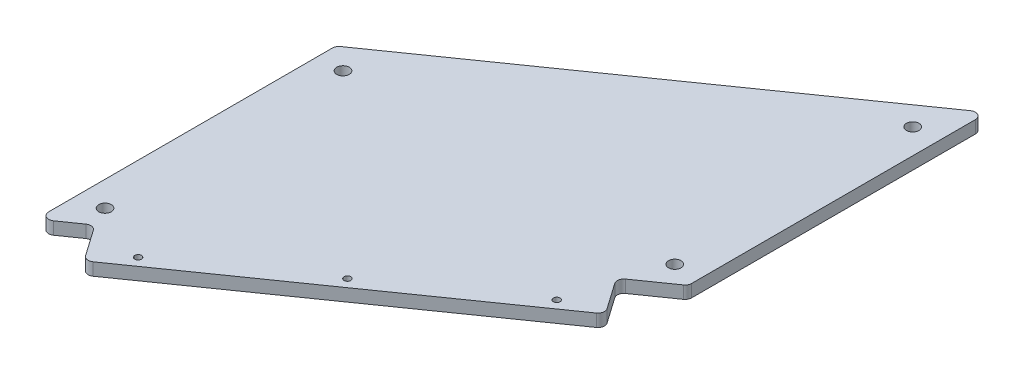
SolidWorks part; units mm, degrees
material "ABS PC"
ref_plane "Front" through (0, 0, 0) normal (0, 0, 1) x (1, 0, 0)
ref_plane "Top" through (0, 0, 0) normal (0, 1, 0) x (1, 0, 0)
ref_plane "Right" through (0, 0, 0) normal (1, 0, 0) x (0, 0, -1)
sketch "Sketch1" plane through (0, 0, 0) normal (0, 1, 0) x (1, 0, 0)
  line L0 (0, 0) -> (0, 359.0634)
  line L1 (0, 0) -> (388.9375, 272.337)
  line L2 (388.9375, 272.337) -> (388.9375, 631.4004)
  line L3 (0, 38.7596) -> (388.9375, 311.0966) construction
  line L4 (0, 54.2634) -> (388.9375, 326.6004) construction
  line L5 (0, 0) -> (-115.0997, 0) construction
  line L6 (0, 359.0634) -> (388.9375, 631.4004)
  dimension "D1" = 388.9375
  dimension "D2" = 145
  dimension "D3" = 31.75
  dimension "D4" = 12.7
  dimension "D5" = 304.8
extrude "Boss-Extrude1" add sketch "Sketch1" along normal blind 12.7
sketch "Sketch2" plane through (0, 12.7, 0) normal (0, 1, 0) x (1, 0, 0)
  line L0 (0, 38.7596) -> (388.9375, 311.0966) construction
  line L1 (0, 359.0634) -> (0, 0) construction
  line L2 (388.9375, 272.337) -> (388.9375, 631.4004) construction
  line L3 (0, 55.1937) -> (388.9375, 327.5306) construction
  line L4 (0, 0) -> (388.9375, 272.337) construction
  line L5 (35.0561, 79.7402) -> (60.9887, 42.7047)
  line L6 (0, 55.1937) -> (35.0561, 79.7402)
  line L7 (0, 55.1937) -> (0, 0)
  line L8 (0, 0) -> (60.9887, 42.7047)
  line L9 (388.9375, 327.5306) -> (346.0997, 297.5353)
  line L10 (346.0997, 297.5353) -> (372.0322, 260.4998)
  line L11 (372.0322, 260.4998) -> (388.9375, 272.337)
  line L12 (388.9375, 272.337) -> (388.9375, 327.5306)
  dimension "D1" = 31.75
  dimension "D2" = 13.462
  dimension "D3" = 74.4534
  dimension "D4" = 20.6375
extrude "Cut-Extrude1" cut sketch "Sketch2" against normal through all
sketch "Sketch3" plane through (0, 12.7, 0) normal (0, 1, 0) x (1, 0, 0)
  line L0 (54.6148, 51.8076) -> (365.6584, 269.6026) construction
  line L1 (60.9887, 42.7047) -> (35.0561, 79.7402) construction
  line L2 (346.0997, 297.5353) -> (372.0322, 260.4998) construction
  line L3 (60.9887, 42.7047) -> (372.0322, 260.4998) construction
  line L4 (25.4, 340.9437) -> (25.4, 99.6437) construction
  line L5 (0, 359.0634) -> (0, 55.1937) construction
  line L6 (363.5375, 580.6004) -> (363.5375, 339.3004) construction
  line L7 (388.9375, 327.5306) -> (388.9375, 631.4004) construction
  circle A0 centre (210.1366, 160.7051) radius 3.3782
  circle A1 centre (334.9754, 248.1181) radius 3.3782
  circle A2 centre (85.2978, 73.292) radius 3.3782
  circle A3 centre (25.4, 99.6437) radius 6.35
  circle A4 centre (25.4, 340.9437) radius 6.35
  circle A5 centre (363.5375, 339.3004) radius 6.35
  circle A6 centre (363.5375, 580.6004) radius 6.35
  dimension "D2" = 6.7564
  dimension "D5" = 12.7
  dimension "D1" = 11.1125
  dimension "D3" = 152.4
  dimension "D4" = 152.4
  dimension "D6" = 25.4
  dimension "D7" = 44.45
  dimension "D8" = 241.3
  dimension "D9" = 25.4
  dimension "D10" = 50.8
extrude "Cut-Extrude2" cut sketch "Sketch3" against normal through all
fillet "Fillet1" radius 6.604 8 edges at (60.9887, 6.35, -42.7047) (372.0322, 6.35, -260.4998) (388.9375, 6.35, -327.5306) (388.9375, 6.35, -631.4004) (0, 6.35, -359.0634) (0, 6.35, -55.1937) (346.0997, 6.35, -297.5353) (35.0561, 6.35, -79.7402)
